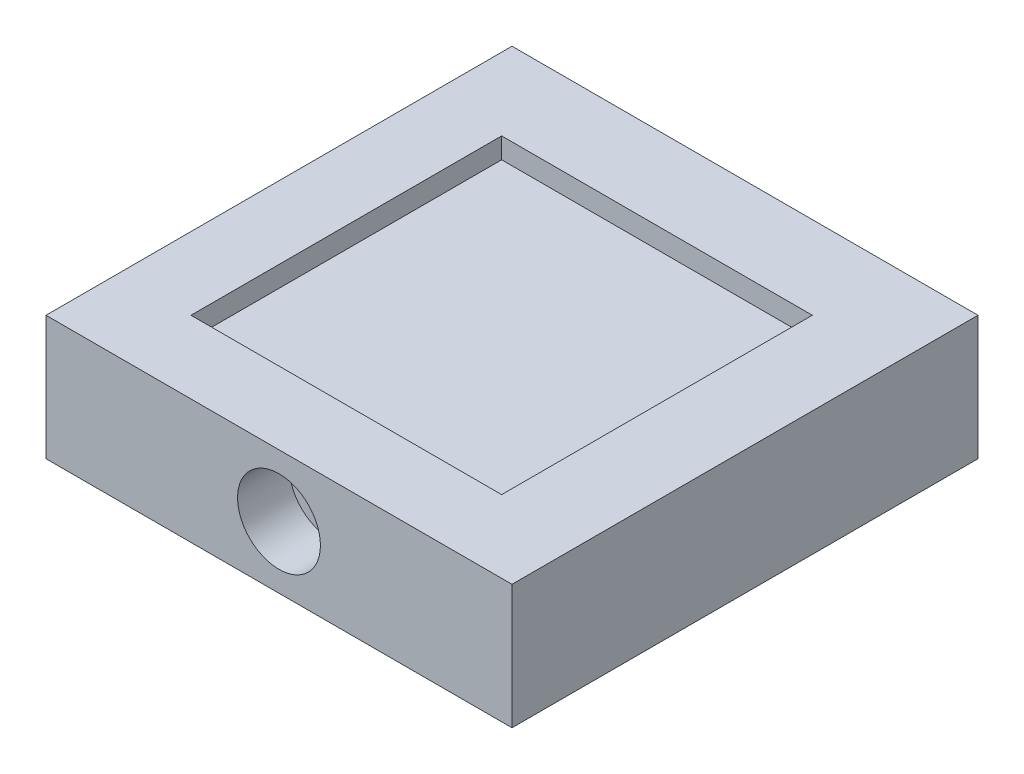
SolidWorks part; units mm, degrees
ref_plane "前视基准面" through (0, 0, 0) normal (0, 0, 1) x (1, 0, 0)
ref_plane "上视基准面" through (0, 0, 0) normal (0, 1, 0) x (1, 0, 0)
ref_plane "右视基准面" through (0, 0, 0) normal (1, 0, 0) x (0, 0, -1)
sketch "草图1" plane through (0, 0, 0) normal (0, 1, 0) x (1, 0, 0)
  line L1 (0, 0) -> (45, 0)
  line L2 (0, 0) -> (0, 45)
  line L3 (0, 45) -> (45, 45)
  line L4 (45, 0) -> (45, 45)
  dimension "D1" = 45
  dimension "D2" = 45
extrude "凸台-拉伸1" add sketch "草图1" along normal blind 12
sketch "草图2" plane through (0, 0, 0) normal (0, 0, 1) x (1, 0, 0)
  circle A0 centre (22.5, 6) radius 4
  dimension "D1" = 8
extrude "切除-拉伸1" cut sketch "草图2" against normal blind 5
sketch "草图3" plane through (0, 0, 0) normal (-1, 0, 0) x (0, 0, 1)
  line L0 (-45, 6) -> (-22.4779, 6) construction
  line L1 (-45, 12) -> (-45, 0) construction
  circle A0 centre (-22.4779, 6) radius 4
  dimension "D1" = 8
extrude "切除-拉伸2" cut sketch "草图3" against normal blind 5
sketch "草图4" plane through (0, 12, 0) normal (0, 1, 0) x (1, 0, 0)
  line L0 (0, 45) -> (0, 0) construction
  line L1 (7, 37) -> (37, 37)
  line L2 (7, 37) -> (7, 7)
  line L3 (7, 7) -> (37, 7)
  line L4 (37, 37) -> (37, 7)
  line L6 (0, 0) -> (45, 0) construction
  dimension "D1" = 30
  dimension "D2" = 7
  dimension "D3" = 7
extrude "切除-拉伸3" cut sketch "草图4" against normal blind 2
